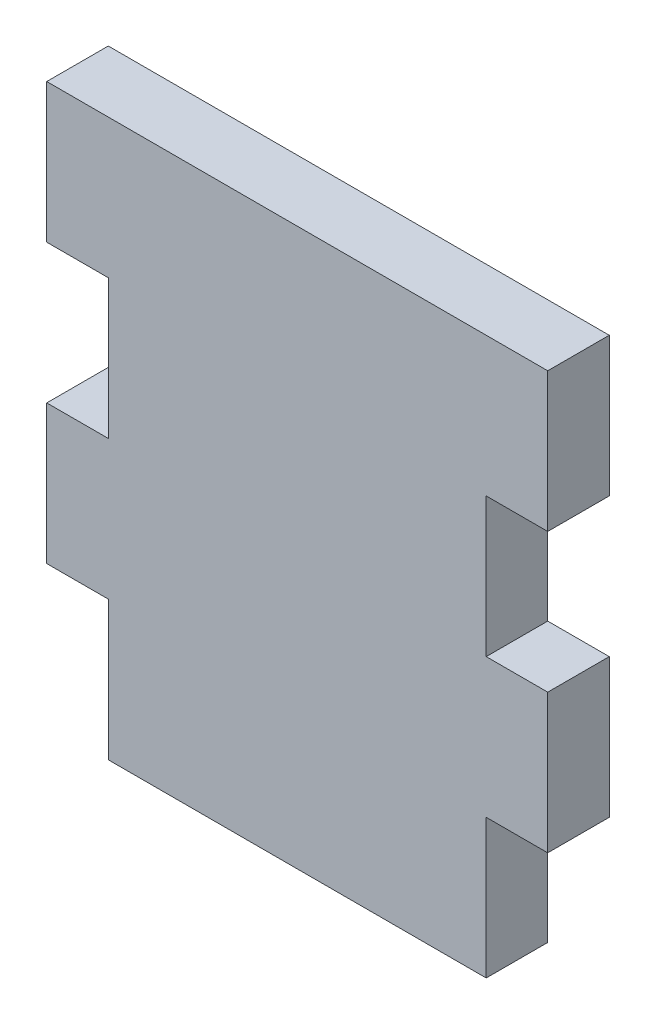
SolidWorks part; units mm, degrees
ref_plane "Front Plane" through (0, 0, 0) normal (0, 0, 1) x (1, 0, 0)
ref_plane "Top Plane" through (0, 0, 0) normal (0, 1, 0) x (1, 0, 0)
ref_plane "Right Plane" through (0, 0, 0) normal (1, 0, 0) x (0, 0, -1)
sketch "Sketch1" plane through (0, 0, 0) normal (0, 0, 1) x (1, 0, 0)
  line L1 (-88.0852, 14.1109) -> (-44.6512, 14.1109)
  line L2 (-88.0852, 14.1109) -> (-88.0852, -34.1491)
  line L3 (-88.0852, -34.1491) -> (-44.6512, -34.1491)
  line L4 (-44.6512, 14.1109) -> (-44.6512, -34.1491)
  dimension "D1" = 48.26
  dimension "D2" = 43.434
extrude "Boss-Extrude1" add sketch "Sketch1" along normal blind 5.334
sketch "Sketch2" plane through (0, 0, 5.334) normal (0, 0, 1) x (1, 0, 0)
  line L0 (-88.0852, 14.1109) -> (-88.0852, -34.1491) construction
  line L1 (-88.0852, -34.1491) -> (-82.7512, -34.1491)
  line L2 (-88.0852, -34.1491) -> (-88.0852, -22.0841)
  line L3 (-88.0852, -22.0841) -> (-82.7512, -22.0841)
  line L4 (-82.7512, -34.1491) -> (-82.7512, -22.0841)
  line L5 (-88.0852, -10.0191) -> (-82.7512, -10.0191)
  line L6 (-88.0852, -10.0191) -> (-88.0852, 2.0459)
  line L7 (-88.0852, 2.0459) -> (-82.7512, 2.0459)
  line L8 (-82.7512, -10.0191) -> (-82.7512, 2.0459)
  line L9 (-82.7512, 2.0459) -> (-82.7512, 14.1109) construction
  line L10 (-44.6512, 14.1109) -> (-88.0852, 14.1109) construction
  line L11 (-82.7512, -10.0191) -> (-82.7512, -22.0841) construction
  line L12 (-66.3682, 14.1109) -> (-66.3682, -34.1491) construction
  line L13 (-88.0852, -34.1491) -> (-44.6512, -34.1491) construction
  line L14 (-49.9852, -10.0191) -> (-49.9852, -22.0841) construction
  line L15 (-49.9852, 2.0459) -> (-49.9852, 14.1109) construction
  line L16 (-49.9852, -10.0191) -> (-49.9852, 2.0459)
  line L17 (-44.6512, 2.0459) -> (-49.9852, 2.0459)
  line L18 (-44.6512, -10.0191) -> (-44.6512, 2.0459)
  line L19 (-44.6512, -10.0191) -> (-49.9852, -10.0191)
  line L20 (-49.9852, -34.1491) -> (-49.9852, -22.0841)
  line L21 (-44.6512, -22.0841) -> (-49.9852, -22.0841)
  line L22 (-44.6512, -34.1491) -> (-44.6512, -22.0841)
  line L23 (-44.6512, -34.1491) -> (-49.9852, -34.1491)
  dimension "D1" = 5.334
extrude "Cut-Extrude1" cut sketch "Sketch2" against normal through all
equation "\"MDF\"= .21in"
equation "\"Foamcore\"= .13in"
equation "\"Gmaterial\"= \"MDF\""
equation "\"D1@Boss-Extrude1\"=\"MDF\""
equation "\"D1@Sketch2\"=\"MDF\""
equation "\"D2@Sketch1\"=\"MDF\"+\"MDF\"+1.29"
